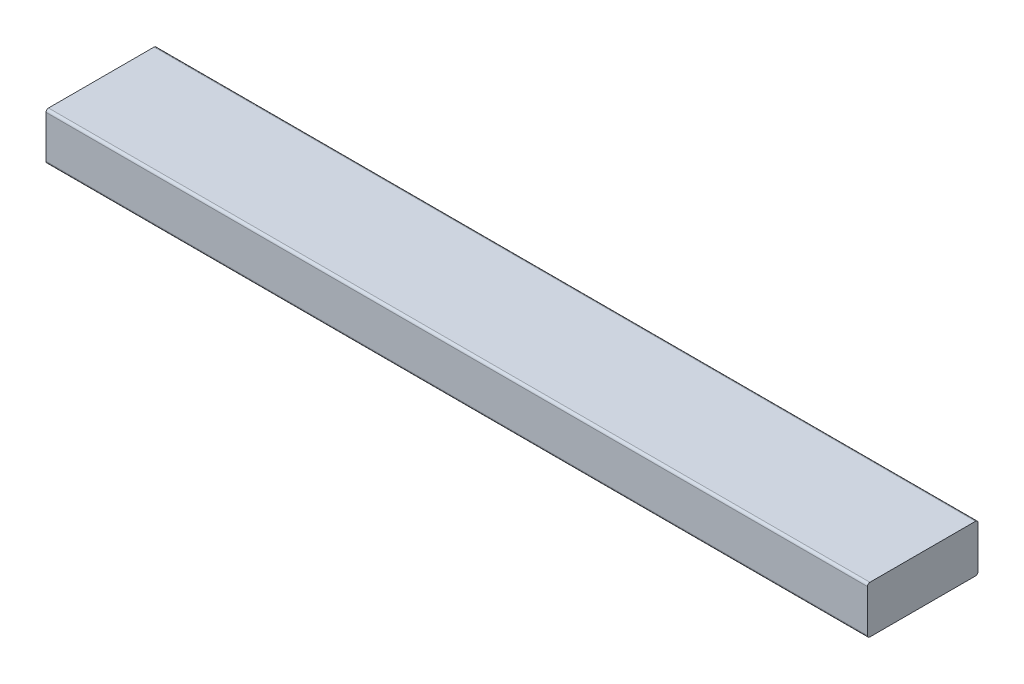
SolidWorks part; units mm, degrees
ref_plane "Front Plane" through (0, 0, 0) normal (0, 0, 1) x (1, 0, 0)
ref_plane "Top Plane" through (0, 0, 0) normal (0, 1, 0) x (1, 0, 0)
ref_plane "Right Plane" through (0, 0, 0) normal (1, 0, 0) x (0, 0, -1)
sketch "Sketch1" plane through (0, 0, 0) normal (1, 0, 0) x (0, 0, -1)
  line L1 (-44.45, -19.05) -> (44.45, -19.05)
  line L2 (-44.45, -19.05) -> (-44.45, 19.05)
  line L3 (-44.45, 19.05) -> (44.45, 19.05)
  line L4 (44.45, -19.05) -> (44.45, 19.05)
  line L5 (-44.45, -19.05) -> (44.45, 19.05) construction
  line L6 (-44.45, 19.05) -> (44.45, -19.05) construction
  point P0 (0, 0)
  dimension "D1" = 38.1
  dimension "D2" = 88.9
extrude "Boss-Extrude1" add sketch "Sketch1" along normal blind 660.4
fillet "Fillet1" radius 2 4 edges at (330.2, 19.05, 44.45) (330.2, 19.05, -44.45) (330.2, -19.05, -44.45) (330.2, -19.05, 44.45)
other "2x4<1>"
